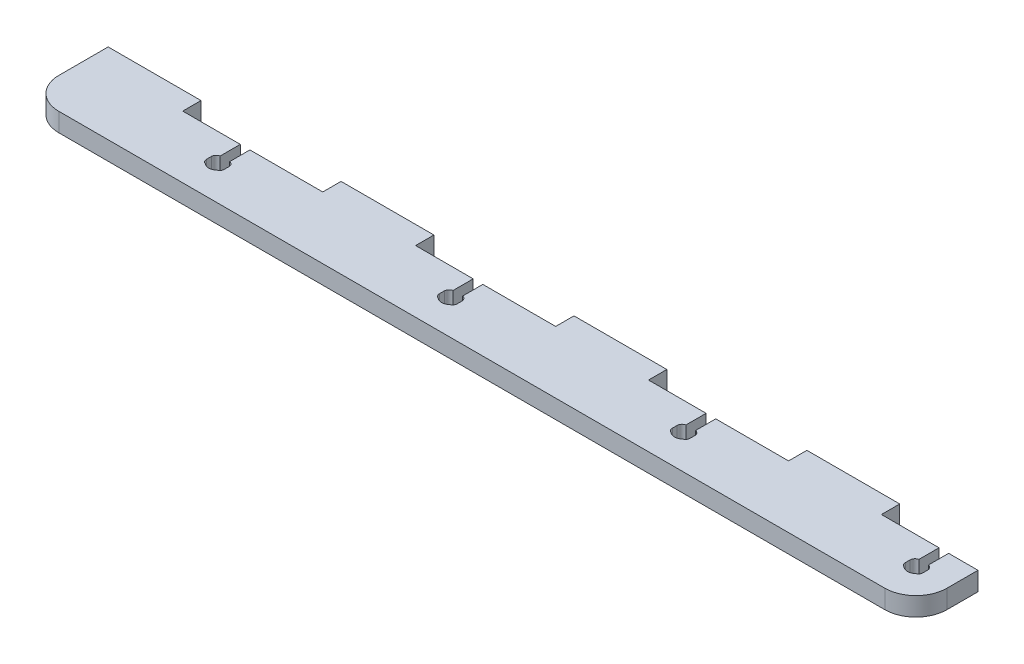
SolidWorks part; units mm, degrees
ref_plane "Alzado" through (0, 0, 0) normal (0, 0, 1) x (1, 0, 0)
ref_plane "Planta" through (0, 0, 0) normal (0, 1, 0) x (1, 0, 0)
ref_plane "Vista lateral" through (0, 0, 0) normal (1, 0, 0) x (0, 0, -1)
sketch "Croquis1" plane through (0, 0, 0) normal (0, 1, 0) x (1, 0, 0)
  line L0 (-93.8619, 15.8484) -> (-93.8619, 22.3486)
  line L1 (-112.4119, 22.3486) -> (-93.8619, 22.3486)
  line L2 (-142.3119, 22.3486) -> (-142.3119, 12.3486)
  line L3 (-132.3119, 2.3486) -> (127.6881, 2.3486)
  line L4 (127.6881, 2.3486) -> (133.6881, 2.3486)
  line L5 (59.2381, 22.3486) -> (82.6881, 22.3486)
  line L6 (-142.3119, 22.3486) -> (-142.3119, 28.2486)
  line L7 (-142.3119, 28.2486) -> (-112.4119, 28.2486)
  line L8 (-112.4119, 22.3486) -> (-112.4119, 28.2486)
  line L9 (-90.7619, 15.8484) -> (-90.7619, 22.3486)
  line L10 (-89.4716, 14.3203) -> (-89.4716, 12.7703)
  line L11 (-90.1804, 11.4684) -> (-90.3497, 11.4684)
  line L12 (-94.4434, 11.4684) -> (-94.2742, 11.4684)
  line L13 (-95.1523, 14.3203) -> (-95.1523, 12.7703)
  line L14 (-15.7619, 22.3486) -> (7.6881, 22.3486)
  line L15 (-67.3119, 28.2486) -> (-37.4119, 28.2486)
  line L16 (-67.3119, 22.3486) -> (-67.3119, 28.2486)
  line L17 (-37.4119, 22.3486) -> (-37.4119, 28.2486)
  line L18 (-18.8619, 15.8484) -> (-18.8619, 22.3486)
  line L19 (-15.7619, 15.8484) -> (-15.7619, 22.3486)
  line L20 (-14.4716, 14.3203) -> (-14.4716, 12.7703)
  line L21 (-15.1804, 11.4684) -> (-15.3497, 11.4684)
  line L22 (-19.4434, 11.4684) -> (-19.2742, 11.4684)
  line L23 (-20.1523, 14.3203) -> (-20.1523, 12.7703)
  line L24 (7.6881, 28.2486) -> (37.5881, 28.2486)
  line L25 (7.6881, 22.3486) -> (7.6881, 28.2486)
  line L26 (37.5881, 22.3486) -> (37.5881, 28.2486)
  line L27 (56.1381, 15.8484) -> (56.1381, 22.3486)
  line L28 (59.2381, 15.8484) -> (59.2381, 22.3486)
  line L29 (60.5284, 14.3203) -> (60.5284, 12.7703)
  line L30 (59.8196, 11.4684) -> (59.6503, 11.4684)
  line L31 (55.5566, 11.4684) -> (55.7258, 11.4684)
  line L32 (54.8477, 14.3203) -> (54.8477, 12.7703)
  line L33 (82.6881, 28.2486) -> (112.5881, 28.2486)
  line L34 (82.6881, 22.3486) -> (82.6881, 28.2486)
  line L35 (112.5881, 22.3486) -> (112.5881, 28.2486)
  line L36 (131.1381, 15.8484) -> (131.1381, 22.3486)
  line L37 (134.2381, 15.8484) -> (134.2381, 22.3486)
  line L38 (135.5284, 14.3203) -> (135.5284, 12.7703)
  line L39 (134.8196, 11.4684) -> (134.6503, 11.4684)
  line L40 (130.5566, 11.4684) -> (130.7258, 11.4684)
  line L41 (129.8477, 14.3203) -> (129.8477, 12.7703)
  line L42 (-90.7619, 22.3486) -> (-67.3119, 22.3486)
  line L43 (37.5881, 22.3486) -> (56.1381, 22.3486)
  line L44 (-37.4119, 22.3486) -> (-18.8619, 22.3486)
  line L45 (134.2381, 22.3486) -> (137.6881, 22.3486)
  line L46 (112.5881, 22.3486) -> (131.1381, 22.3486)
  line L50 (137.6881, 22.3486) -> (143.6881, 22.3486)
  line L53 (143.6881, 22.3486) -> (143.6881, 12.3486)
  arc A0 (-89.4716, 14.3203) -> (-90.7619, 15.8484) centre (-91.0216, 14.3203) ccw
  arc A1 (-90.1804, 11.4684) -> (-89.4716, 12.7703) centre (-91.0216, 12.7703) ccw
  arc A2 (-94.2742, 11.4684) -> (-90.3497, 11.4684) centre (-92.3119, 13.4299) ccw
  arc A3 (-94.4434, 11.4684) -> (-95.1523, 12.7703) centre (-93.6023, 12.7703) cw
  arc A4 (-95.1523, 14.3203) -> (-93.8619, 15.8484) centre (-93.6023, 14.3203) cw
  arc A5 (-14.4716, 14.3203) -> (-15.7619, 15.8484) centre (-16.0216, 14.3203) ccw
  arc A6 (-15.1804, 11.4684) -> (-14.4716, 12.7703) centre (-16.0216, 12.7703) ccw
  arc A7 (-19.2742, 11.4684) -> (-15.3497, 11.4684) centre (-17.3119, 13.4299) ccw
  arc A8 (-19.4434, 11.4684) -> (-20.1523, 12.7703) centre (-18.6023, 12.7703) cw
  arc A9 (-20.1523, 14.3203) -> (-18.8619, 15.8484) centre (-18.6023, 14.3203) cw
  arc A10 (60.5284, 14.3203) -> (59.2381, 15.8484) centre (58.9784, 14.3203) ccw
  arc A11 (59.8196, 11.4684) -> (60.5284, 12.7703) centre (58.9784, 12.7703) ccw
  arc A12 (55.7258, 11.4684) -> (59.6503, 11.4684) centre (57.6881, 13.4299) ccw
  arc A13 (55.5566, 11.4684) -> (54.8477, 12.7703) centre (56.3977, 12.7703) cw
  arc A14 (54.8477, 14.3203) -> (56.1381, 15.8484) centre (56.3977, 14.3203) cw
  arc A15 (135.5284, 14.3203) -> (134.2381, 15.8484) centre (133.9784, 14.3203) ccw
  arc A16 (134.8196, 11.4684) -> (135.5284, 12.7703) centre (133.9784, 12.7703) ccw
  arc A17 (130.7258, 11.4684) -> (134.6503, 11.4684) centre (132.6881, 13.4299) ccw
  arc A18 (130.5566, 11.4684) -> (129.8477, 12.7703) centre (131.3977, 12.7703) cw
  arc A19 (129.8477, 14.3203) -> (131.1381, 15.8484) centre (131.3977, 14.3203) cw
  arc A20 (143.6881, 12.3486) -> (133.6881, 2.3486) centre (133.6881, 12.3486) cw
  arc A21 (-132.3119, 2.3486) -> (-142.3119, 12.3486) centre (-132.3119, 12.3486) cw
  point P7 (-92.4119, 22.3486)
  point P90 (137.6881, 2.3486)
  dimension "D7" = 6
  dimension "D8" = 10
  dimension "D1" = 280
  dimension "D2" = 20
  dimension "D3" = 29.9
  dimension "D4" = 5.9
  dimension "D5" = 20
  dimension "D9" = 29.9
  dimension "D6" = 29.9
  dimension "D10" = 29.9
extrude "Saliente-Extruir1" add sketch "Croquis1" along normal blind 6
